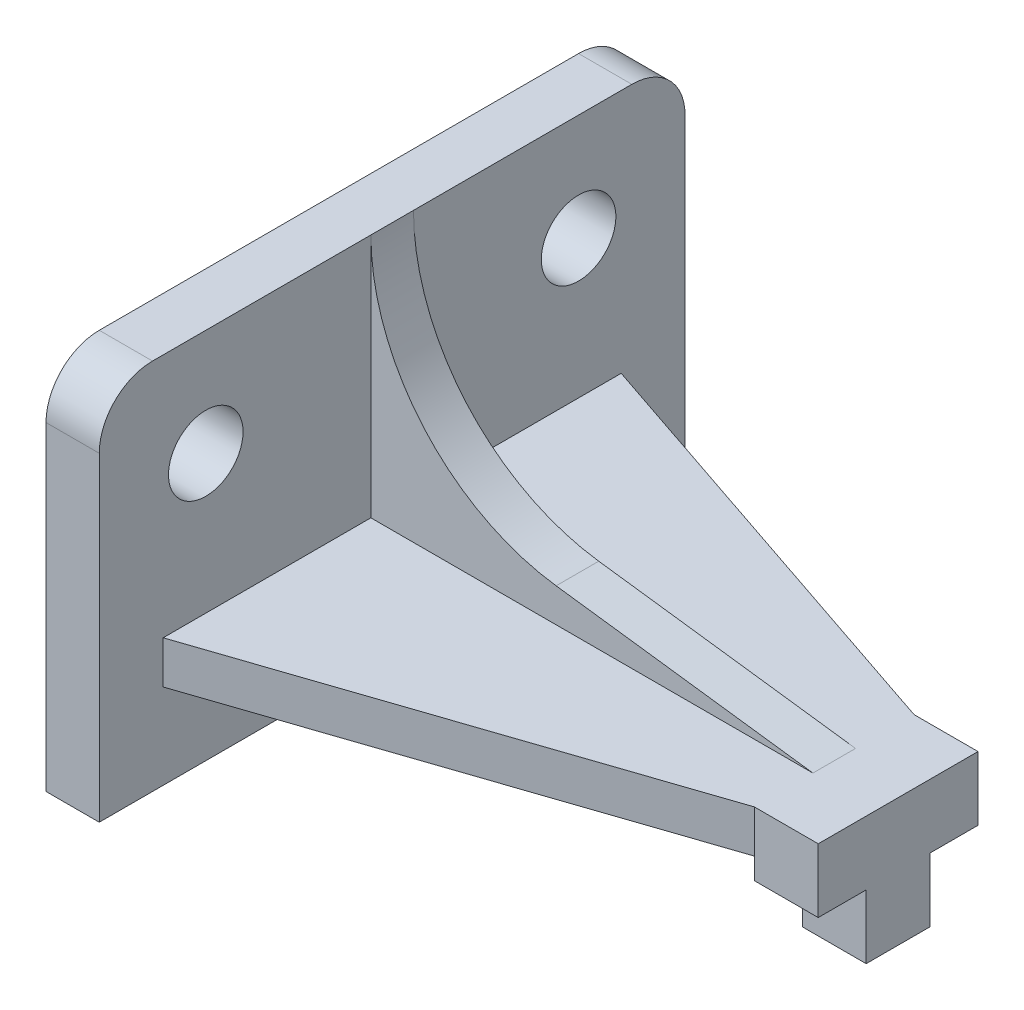
SolidWorks part; units mm, degrees
ref_plane "Front Plane" through (0, 0, 0) normal (0, 0, 1) x (1, 0, 0)
ref_plane "Top Plane" through (0, 0, 0) normal (0, 1, 0) x (1, 0, 0)
ref_plane "Right Plane" through (0, 0, 0) normal (1, 0, 0) x (0, 0, -1)
sketch "Sketch1" plane through (0, 0, 0) normal (1, 0, 0) x (0, 0, -1)
  line L0 (0, 55) -> (0, -55) construction
  line L1 (-45, 35) -> (45, 35)
  line L2 (-55, 25) -> (-55, -35)
  line L3 (-55, -35) -> (55, -35)
  line L4 (55, 25) -> (55, -35)
  line L5 (-55, 35) -> (55, -35) construction
  line L6 (-55, -35) -> (55, 35) construction
  arc A0 (45, 35) -> (55, 25) centre (45, 25) cw
  arc A1 (-45, 35) -> (-55, 25) centre (-45, 25) ccw
  circle A2 centre (-35, 15) radius 7
  circle A4 centre (35, 15) radius 7
  point P0 (0, 0)
  dimension "D3" = 10
  dimension "D4" = 14
  dimension "D1" = 110
  dimension "D2" = 70
  dimension "D5" = 20
  dimension "D6" = 20
extrude "Boss-Extrude1" add sketch "Sketch1" along normal blind 10
ref_plane "Plane1" through (105, 0, 0) normal (-1, 0, 0) x (0, 0, 1)
sketch "Sketch4" plane through (105, 0, 0) normal (-1, 0, 0) x (0, 0, 1)
  line L0 (6, -35) -> (6, -23)
  line L1 (55, -35) -> (-55, -35) construction
  line L2 (6, -23) -> (15, -23)
  line L3 (15, -23) -> (15, -11)
  line L4 (15, -11) -> (-15, -11)
  line L5 (-15, -11) -> (-15, -23)
  line L6 (-15, -23) -> (-6, -23)
  line L7 (-6, -23) -> (-6, -35)
  line L8 (-6, -35) -> (6, -35)
  line L9 (0, 0) -> (0, -48.6079) construction
  dimension "D1" = 30
  dimension "D2" = 12
  dimension "D3" = 12
  dimension "D4" = 12
extrude "Boss-Extrude2" add sketch "Sketch4" along normal blind 12 separate body
sketch "Sketch5" plane through (0, 0, 0) normal (0, 0, 1) x (1, 0, 0)
  line L0 (44.784, -4.6585) -> (93, -11)
  line L2 (10, 25) -> (10, -35) construction
  line L4 (93, -15) -> (10, -15)
  line L7 (10, 35) -> (10, -15)
  line L8 (93, -23) -> (93, -11) construction
  line L9 (93, -15) -> (93, -11)
  line L10 (10, -35) -> (0, -35) construction
  arc A0 (10, 35) -> (44.784, -4.6585) centre (50, 35) ccw
  dimension "D1" = 40
  dimension "D2" = 20
extrude "Boss-Extrude3" add sketch "Sketch5" along normal mid plane 8
sketch "Sketch6" plane through (0, 0, 0) normal (0, 1, 0) x (1, 0, 0)
  line L0 (93, -15) -> (93, -4) construction
  line L1 (93, 4) -> (93, 15) construction
  line L2 (93, -4) -> (93, 4) construction
  line L3 (93, -15) -> (93, -4)
  line L4 (93, 4) -> (93, 15)
  line L5 (93, -4) -> (93, 4)
  line L6 (93, 15) -> (10, 43)
  line L7 (10, 45) -> (10, 4) construction
  line L8 (10, 43) -> (10, -43)
  line L9 (10, -4) -> (10, -45) construction
  line L10 (10, -43) -> (93, -15)
  line L11 (10, 55) -> (0, 55) construction
  line L12 (10, -55) -> (0, -55) construction
  dimension "D1" = 12
  dimension "D2" = 12
extrude "Boss-Extrude4" add sketch "Sketch6" along normal mid plane 8 from surface at -15 starting at face at (51.5, -15, 0)
